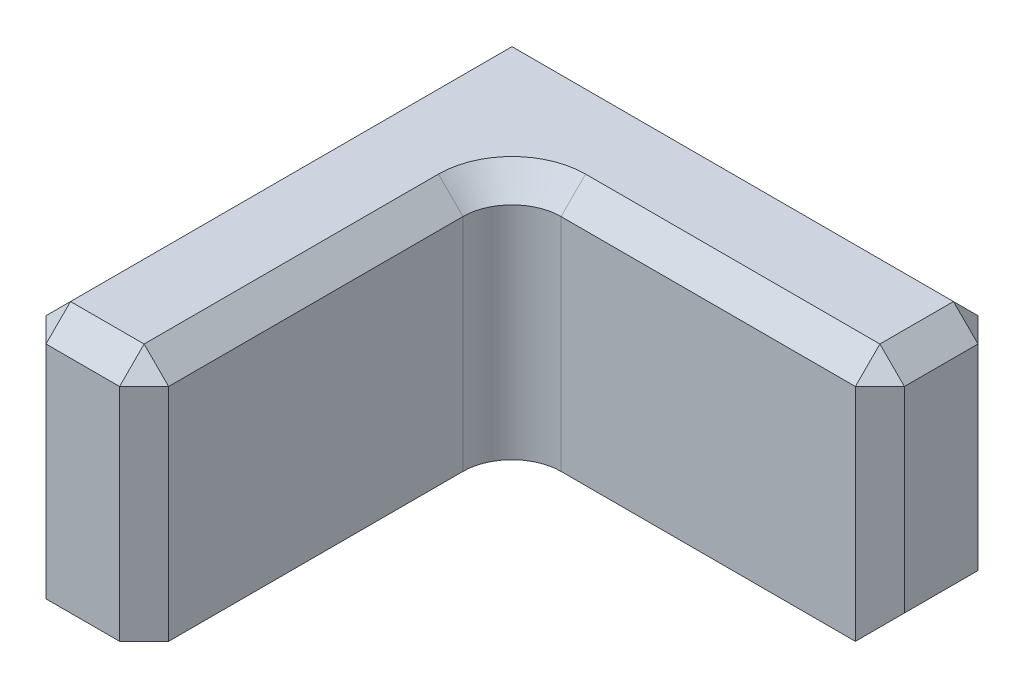
SolidWorks part; units mm, degrees
ref_plane "前视基准面" through (0, 0, 0) normal (0, 0, 1) x (1, 0, 0)
ref_plane "上视基准面" through (0, 0, 0) normal (0, 1, 0) x (1, 0, 0)
ref_plane "右视基准面" through (0, 0, 0) normal (1, 0, 0) x (0, 0, -1)
other "Configuration Table"
sketch "草图1" plane through (0, 0, 0) normal (0, 1, 0) x (1, 0, 0)
  line L1 (0, 0) -> (5, 0)
  line L2 (0, 0) -> (0, -20)
  line L3 (0, -20) -> (5, -20)
  line L4 (5, -5) -> (5, -20)
  line L5 (0, 0) -> (20, 0)
  line L6 (0, 0) -> (0, -5)
  line L7 (5, -5) -> (20, -5)
  line L8 (20, 0) -> (20, -5)
  dimension "D1" = 5
  dimension "D2" = 5
  dimension "D3" = 15
  dimension "D4" = 15
extrude "凸台-拉伸1" add sketch "草图1" along normal blind 10 contours L8 L5 L1 L2 L3 L4 L7
fillet "圆角1" radius 2 1 edges at (5, 5, 5)
chamfer "倒角1" distance 1 angle 45 13 edges at (20, 5, 5) (20, 0, 2.5) (20, 5, 0) (13.5, 10, 5) (5.5858, 10, 5.5858) (5, 10, 13.5) (20, 10, 2.5) (10, 10, 0) (0, 5, 0) (0, 10, 10) (0, 5, 20) (2.5, 10, 20) (5, 5, 20)
